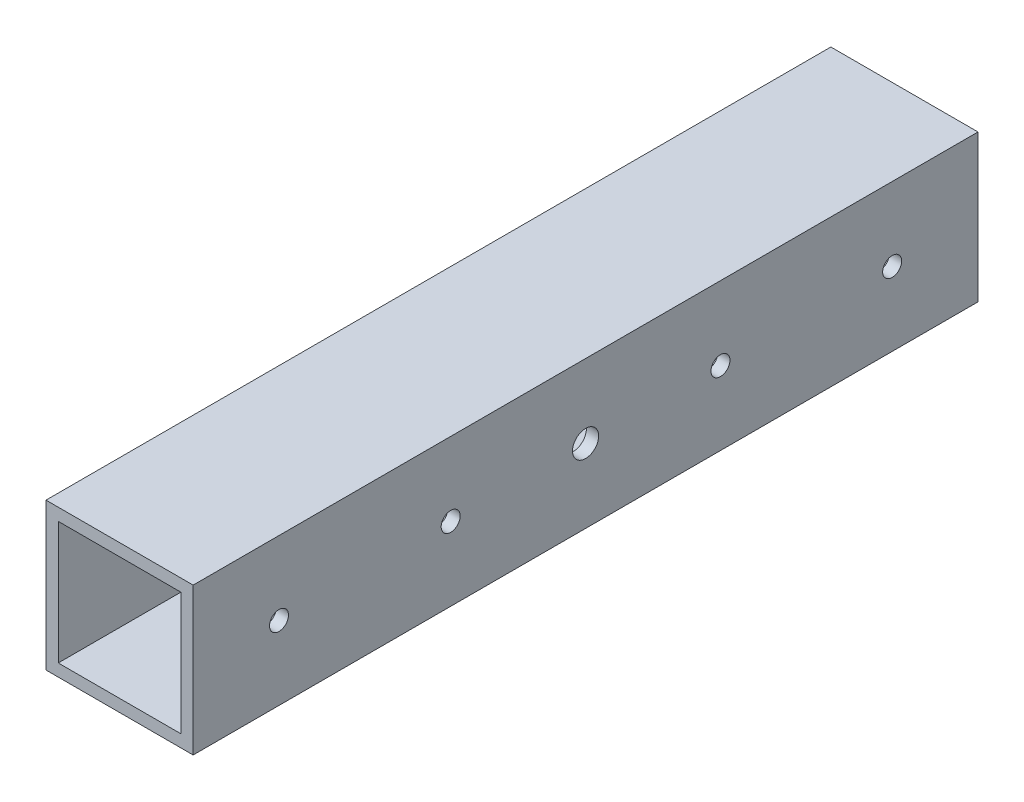
SolidWorks part; units mm, degrees
material "6061 Alloy"
ref_plane "Front Plane" through (0, 0, 0) normal (0, 0, 1) x (1, 0, 0)
ref_plane "Top Plane" through (0, 0, 0) normal (0, 1, 0) x (1, 0, 0)
ref_plane "Right Plane" through (0, 0, 0) normal (1, 0, 0) x (0, 0, -1)
sketch "Sketch1" plane through (0, 0, 0) normal (0, 0, 1) x (1, 0, 0)
  line L0 (-15.875, 15.875) -> (15.875, 15.875)
  line L1 (-19.05, -19.05) -> (19.05, -19.05)
  line L2 (-19.05, -19.05) -> (-19.05, 19.05)
  line L3 (-19.05, 19.05) -> (19.05, 19.05)
  line L4 (19.05, -19.05) -> (19.05, 19.05)
  line L5 (-19.05, -19.05) -> (19.05, 19.05) construction
  line L6 (-19.05, 19.05) -> (19.05, -19.05) construction
  line L7 (15.875, -15.875) -> (15.875, 15.875)
  line L8 (-15.875, -15.875) -> (15.875, -15.875)
  line L9 (-15.875, -15.875) -> (-15.875, 15.875)
  point P0 (0, 0)
  dimension "D1" = 38.1
  dimension "D2" = 38.1
  dimension "D3" = 3.175
extrude "Boss-Extrude1" add sketch "Sketch1" along normal blind 203.2
sketch "Sketch2" plane through (-19.05, 0, 0) normal (-1, 0, 0) x (0, 0, 1)
  line L0 (0, 19.05) -> (0, -19.05) construction
  line L1 (203.2, 19.05) -> (203.2, -19.05) construction
  point P0 (22.225, 0)
  point P1 (66.675, 0)
  point P2 (136.525, 0)
  point P3 (180.975, 0)
  dimension "D1" = 44.45
  dimension "D2" = 22.225
  dimension "D3" = 22.225
  dimension "D4" = 44.45
hole_wizard "#10 (0.1935) Diameter Hole1" positions "Sketch3" profile "Sketch4" hole size "#10" standard "ANSI Inch" end condition through all
sketch "Sketch3" plane through (-19.05, 0, 0) normal (-1, 0, 0) x (0, 0, 1)
  point P0 (22.225, 0)
  point P3 (66.675, 0)
  point P6 (136.525, 0)
  point P9 (180.975, 0)
sketch "Sketch4" plane through (-19.05, 0, 22.225) normal (0, 1, 0) x (0, 0, 1)
  line L0 (0, 0) -> (0, 38.1)
  line L1 (0, 38.1) -> (2.4574, 38.1)
  line L2 (2.4574, 38.1) -> (2.4574, 0)
  line L5 (2.4574, 0) -> (0, 0)
  line L11 (0, -6.35) -> (0, 107.95) construction
  dimension "Thru Hole Dia." = 4.9149
  dimension "Thru Hole Depth" = 38.1
hole_wizard "1/4 Clearance Hole1" positions "Sketch5" profile "Sketch6" hole size "1/4" standard "ANSI Inch" end condition through all
sketch "Sketch5" plane through (19.05, 0, 0) normal (1, 0, 0) x (0, 0, -1)
  line L0 (-203.2, 0) -> (0, 0) construction
  line L1 (-203.2, -19.05) -> (-203.2, 19.05) construction
  line L3 (-203.2, 0) -> (0, 0) construction
  line L4 (0, -19.05) -> (0, 19.05) construction
  point P0 (-101.6, 0)
sketch "Sketch6" plane through (19.05, 0, 101.6) normal (0, 1, 0) x (0, 0, -1)
  line L0 (0, 0) -> (0, 38.1)
  line L1 (0, 38.1) -> (3.3782, 38.1)
  line L2 (3.3782, 38.1) -> (3.3782, 0)
  line L5 (3.3782, 0) -> (0, 0)
  line L11 (0, -6.35) -> (0, 107.95) construction
  dimension "Thru Hole Dia." = 6.7564
  dimension "Thru Hole Depth" = 38.1
